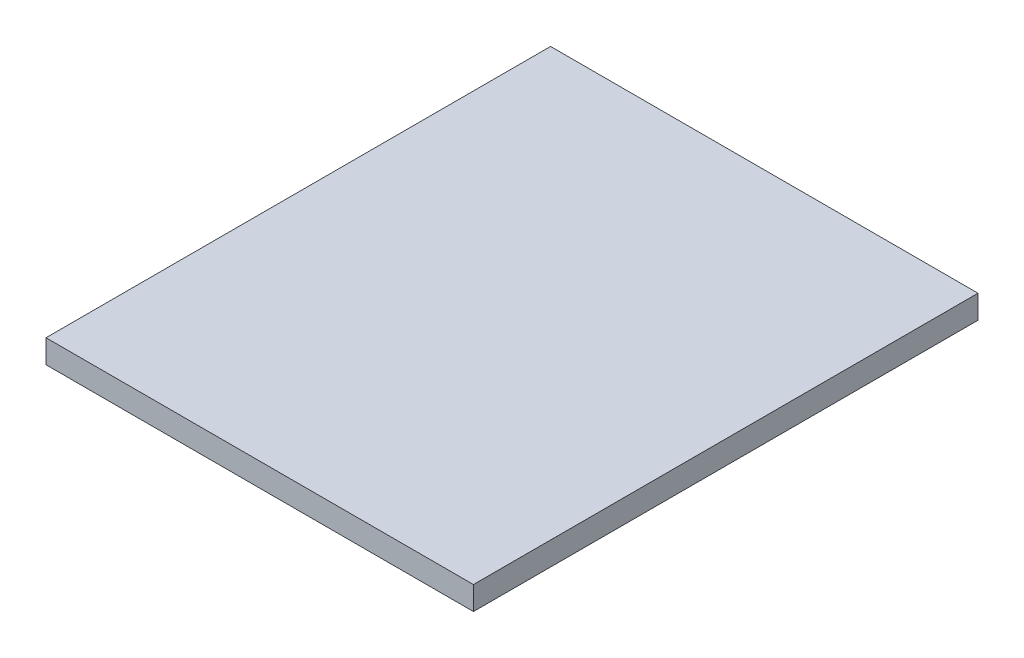
SolidWorks part; units mm, degrees
ref_plane "Front Plane" through (0, 0, 0) normal (0, 0, 1) x (1, 0, 0)
ref_plane "Top Plane" through (0, 0, 0) normal (0, 1, 0) x (1, 0, 0)
ref_plane "Right Plane" through (0, 0, 0) normal (1, 0, 0) x (0, 0, -1)
sketch "Sketch1" plane through (0, 0, 0) normal (0, 1, 0) x (1, 0, 0)
  line L1 (23.1717, -27.3522) -> (-23.1717, -27.3522)
  line L2 (23.1717, -27.3522) -> (23.1717, 27.3522)
  line L3 (23.1717, 27.3522) -> (-23.1717, 27.3522)
  line L4 (-23.1717, -27.3522) -> (-23.1717, 27.3522)
  line L5 (23.1717, -27.3522) -> (-23.1717, 27.3522) construction
  line L6 (23.1717, 27.3522) -> (-23.1717, -27.3522) construction
  point P0 (0, 0)
extrude "Boss-Extrude1" add sketch "Sketch1" along normal blind 2.54
sketch "Sketch2" plane through (0, 0, 0) normal (0, -1, 0) x (1, 0, 0)
  line L0 (0, 0) -> (-40.9706, 0)
pattern_linear "LPattern1" count 6 spacing 50 along (-1, 0, 0) of "Boss-Extrude1"
